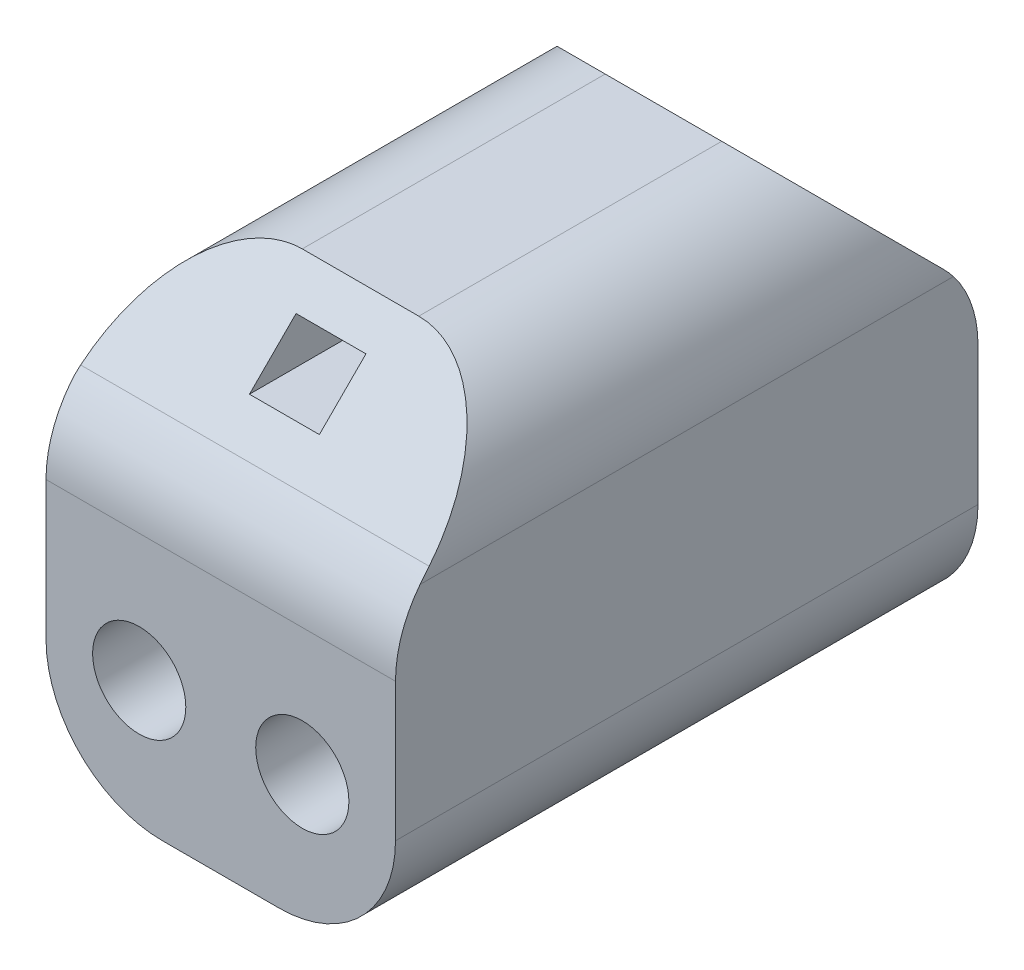
SolidWorks part; units mm, degrees
ref_plane "Front Plane" through (0, 0, 0) normal (0, 0, 1) x (1, 0, 0)
ref_plane "Top Plane" through (0, 0, 0) normal (0, 1, 0) x (1, 0, 0)
ref_plane "Right Plane" through (0, 0, 0) normal (1, 0, 0) x (0, 0, -1)
sketch "Sketch1" plane through (0, 0, 0) normal (1, 0, 0) x (0, 0, -1)
  line L0 (-31.3244, -10.2167) -> (-37.3244, -16.2167)
  line L1 (-37.3244, -16.2167) -> (-37.3244, -29.2167)
  line L2 (-37.3244, -29.2167) -> (-12.3244, -29.2167)
  line L3 (-12.3244, -29.2167) -> (-12.3244, -16.2167)
  line L4 (-12.3244, -16.2167) -> (-18.3244, -10.2167)
  line L5 (-18.3244, -10.2167) -> (-31.3244, -10.2167)
  dimension "D1" = 45
  dimension "D2" = 45
  dimension "D3" = 13
  dimension "D4" = 6
  dimension "D5" = 6
  dimension "D6" = 25
  dimension "D7" = 6
extrude "Boss-Extrude1" add sketch "Sketch1" along normal mid plane 15
fillet "Fillet3" radius 5 2 edges at (0, -16.2167, 37.3244) (0, -16.2167, 12.3244)
sketch "Sketch4" plane through (0, 0, 0) normal (0, 0, 1) x (1, 0, 0)
  line L0 (-7.5, -18.2878) -> (-7.5, -29.2167) construction
  line L1 (7.5, -18.2878) -> (7.5, -29.2167) construction
  line L2 (-7.5, -10.2167) -> (-7.5, -14.7523) construction
  line L3 (-1.5, -11.4845) -> (1.5, -11.4845)
  line L4 (-1.5, -11.4845) -> (-1.5, -13.4845)
  line L5 (-1.5, -13.4845) -> (1.5, -13.4845)
  line L6 (1.5, -11.4845) -> (1.5, -13.4845)
  line L7 (-1.5, -11.4845) -> (1.5, -13.4845) construction
  line L8 (-1.5, -13.4845) -> (1.5, -11.4845) construction
  line L9 (7.5, -10.2167) -> (7.5, -14.7523) construction
  circle A0 centre (-3.5, -23.7523) radius 2
  circle A1 centre (3.5, -23.7523) radius 2
  point P8 (-7.5, -23.7523)
  point P11 (0, -12.4845)
  point P16 (-7.5, -12.4845)
  dimension "D1" = 4
  dimension "D2" = 4
  dimension "D3" = 4
  dimension "D4" = 4
  dimension "D5" = 3
  dimension "D6" = 2
  dimension "D7" = 6
  dimension "D8" = 6
extrude "Cut-Extrude1" cut sketch "Sketch4" against normal mid plane 200
fillet "Fillet4" radius 5 2 edges at (-7.5, -29.2167, 24.8244) (7.5, -29.2167, 24.8244)
fillet "Fillet5" radius 5 2 edges at (7.5, -10.2167, 24.8244) (-7.5, -10.2167, 24.8244)
